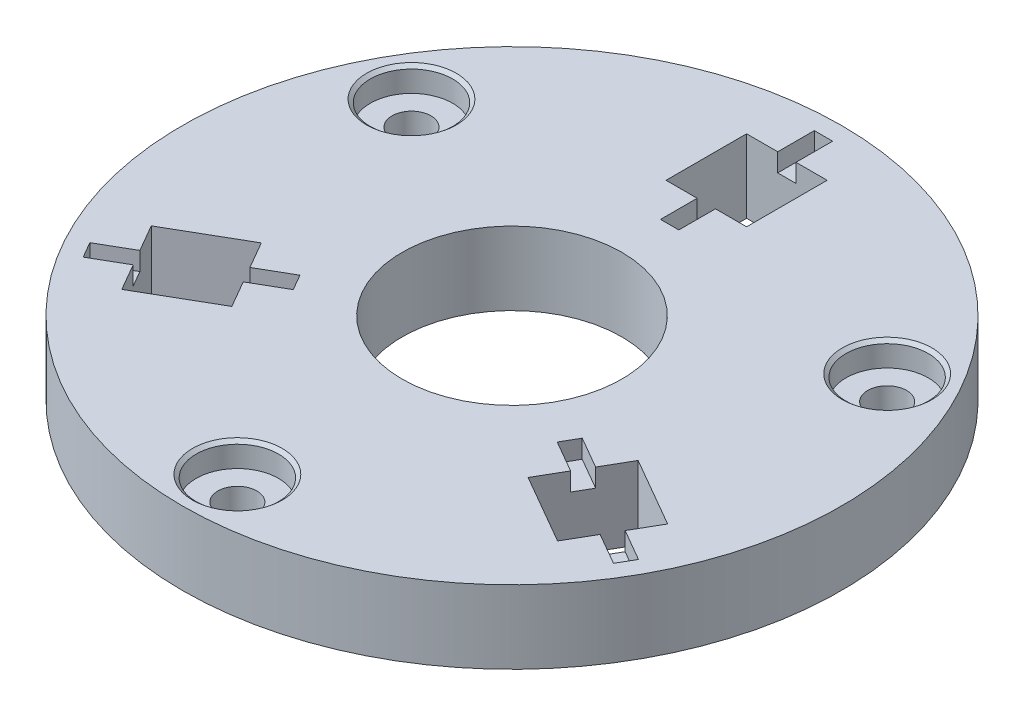
SolidWorks part; units mm, degrees
ref_plane "Front Plane" through (0, 0, 0) normal (0, 0, 1) x (1, 0, 0)
ref_plane "Top Plane" through (0, 0, 0) normal (0, 1, 0) x (1, 0, 0)
ref_plane "Right Plane" through (0, 0, 0) normal (1, 0, 0) x (0, 0, -1)
sketch "Sketch1" plane through (0, 0, 0) normal (0, 1, 0) x (1, 0, 0)
  circle A0 centre (0, 0) radius 57.15
  dimension "D1" = 114.3
extrude "Boss-Extrude1" add sketch "Sketch1" along normal blind 12.7
sketch "Sketch2" plane through (0, 12.7, 0) normal (0, 1, 0) x (1, 0, 0)
  circle A0 centre (0, 0) radius 19.05
  dimension "D1" = 38.1
extrude "Cut-Extrude1" cut sketch "Sketch2" against normal blind 76.2
hole_wizard "CBORE for 1/4 Binding Head Machine Screw1" positions "3DSketch1" profile "Sketch4" counterbore size "1/4" standard "ANSI Inch" end condition through all
sketch3d "3DSketch1"
  line L0 (-41.2445, 12.7, -23.8125) -> (41.2445, 12.7, -23.8125) construction
  line L2 (-41.2445, 12.7, -23.8125) -> (0, 12.7, 47.625) construction
  line L4 (0, 12.7, 47.625) -> (41.2445, 12.7, -23.8125) construction
  circle A2 centre (0, 12.7, 0) radius 47.625 construction
  point P0 (-41.2445, 12.7, -23.8125)
  point P4 (41.2445, 12.7, -23.8125)
  point P8 (0, 12.7, 47.625)
  point P33 (0, 60.325, 0)
  dimension "D1" = 95.25
sketch "Sketch4" plane through (-41.2445, 12.7, -23.8125) normal (1, 0, 0) x (0, 0, 1)
  line L0 (0, 0) -> (0, 12.7)
  line L1 (0, 12.7) -> (3.3782, 12.7)
  line L3 (3.3782, 12.7) -> (3.3782, 4.191)
  line L4 (7.1437, 4.191) -> (3.3782, 4.191)
  line L5 (7.1437, 4.191) -> (7.1437, 0.5328)
  line L6 (7.1437, 0.5328) -> (7.7788, 0)
  line L7 (7.7788, 0) -> (0, 0)
  line L8 (-7.1437, 0.5328) -> (-7.7788, 0) construction
  line L11 (0, -6.35) -> (0, 107.95) construction
  dimension "Thru Hole Dia." = 6.7564
  dimension "Thru Hole Depth" = 12.7
  dimension "C'Bore Dia." = 14.2875
  dimension "C'Bore Depth" = 4.191
  dimension "Near C'Sink Dia." = 15.5575
  dimension "Near C'Sink Angle" = 100
sketch "Sketch5" plane through (0, 12.7, 0) normal (0, 1, 0) x (1, 0, 0)
  line L0 (-44.7713, -17.7831) -> (-32.6729, -10.7981)
  line L5 (32.6729, -10.7981) -> (44.7713, -17.7831)
  line L6 (32.6729, -10.7981) -> (25.6879, -22.8965)
  line L7 (25.6879, -22.8965) -> (37.7863, -29.8815)
  line L8 (44.7713, -17.7831) -> (37.7863, -29.8815)
  line L13 (-6.985, 47.6647) -> (6.985, 47.6647)
  line L14 (-6.985, 47.6647) -> (-6.985, 33.6947)
  line L15 (-6.985, 33.6947) -> (6.985, 33.6947)
  line L16 (6.985, 47.6647) -> (6.985, 33.6947)
  line L17 (-32.6729, -10.7981) -> (-25.6879, -22.8965)
  line L18 (-25.6879, -22.8965) -> (-37.7863, -29.8815)
  line L19 (-37.7863, -29.8815) -> (-44.7713, -17.7831)
  line L20 (44.7713, -17.7831) -> (32.6729, -10.7981)
  line L22 (6.985, 42.2672) -> (6.985, 39.0922)
  line L26 (-6.985, 42.2672) -> (-6.985, 39.0922)
  line L29 (44.7713, -17.7831) -> (37.7863, -29.8815)
  line L30 (37.7863, -29.8815) -> (25.6879, -22.8965)
  line L31 (32.6729, -10.7981) -> (25.6879, -22.8965)
  line L32 (40.0969, -15.0844) -> (37.3473, -13.4969)
  line L36 (33.1119, -27.1828) -> (30.3623, -25.5953)
  line L40 (-37.7863, -29.8815) -> (-25.6879, -22.8965)
  line L41 (-37.7863, -29.8815) -> (-44.7713, -17.7831)
  line L42 (-44.7713, -17.7831) -> (-32.6729, -10.7981)
  line L43 (-25.6879, -22.8965) -> (-32.6729, -10.7981)
  line L44 (-33.1119, -27.1828) -> (-30.3623, -25.5953)
  line L48 (-40.0969, -15.0844) -> (-37.3473, -13.4969)
  circle A0 centre (0, 0) radius 41.275 construction
  point P2 (-38.7221, -14.2906)
  point P15 (6.985, 40.6797)
  point P16 (0, 47.6647)
  point P18 (-31.7371, -26.389)
  point P23 (38.7221, -14.2906)
  point P24 (31.7371, -26.389)
  point P57 (0, 0)
  dimension "D2" = 82.55
  dimension "D1" = 120
  dimension "D3" = 120
  dimension "D4" = 13.97
extrude "Cut-Extrude2" cut sketch "Sketch5" against normal blind 12.7 contours L16 L13 L14 L15 | L19 L18 L40 L17 L0 L42 | L8 L5 L20 L6 L7 L30 | L22
sketch "Sketch7" plane through (0, 12.7, 0) normal (0, 1, 0) x (1, 0, 0)
  line L0 (-6.985, 47.6647) -> (6.985, 47.6647) construction
  line L1 (-1.5875, 47.6647) -> (1.5875, 47.6647)
  line L2 (-1.5875, 47.6647) -> (-1.5875, 54.0147)
  line L3 (-1.5875, 54.0147) -> (1.5875, 54.0147)
  line L4 (1.5875, 47.6647) -> (1.5875, 54.0147)
  line L5 (-6.985, 33.6947) -> (6.985, 33.6947) construction
  line L6 (-1.5875, 33.6947) -> (1.5875, 33.6947)
  line L7 (-1.5875, 33.6947) -> (-1.5875, 27.3447)
  line L8 (-1.5875, 27.3447) -> (1.5875, 27.3447)
  line L9 (1.5875, 33.6947) -> (1.5875, 27.3447)
  line L10 (42.0726, -22.4575) -> (47.5718, -25.6325)
  line L11 (42.0726, -22.4575) -> (40.4851, -25.2071)
  line L12 (40.4851, -25.2071) -> (45.9843, -28.3821)
  line L13 (47.5718, -25.6325) -> (45.9843, -28.3821)
  line L14 (29.9742, -15.4725) -> (24.4749, -12.2975)
  line L15 (29.9742, -15.4725) -> (28.3867, -18.2221)
  line L16 (28.3867, -18.2221) -> (22.8874, -15.0471)
  line L17 (24.4749, -12.2975) -> (22.8874, -15.0471)
  line L18 (-40.4851, -25.2071) -> (-45.9843, -28.3821)
  line L19 (-40.4851, -25.2071) -> (-42.0726, -22.4575)
  line L20 (-42.0726, -22.4575) -> (-47.5718, -25.6325)
  line L21 (-45.9843, -28.3821) -> (-47.5718, -25.6325)
  line L22 (-28.3867, -18.2221) -> (-22.8874, -15.0471)
  line L23 (-28.3867, -18.2221) -> (-29.9742, -15.4725)
  line L24 (-29.9742, -15.4725) -> (-24.4749, -12.2975)
  line L25 (-22.8874, -15.0471) -> (-24.4749, -12.2975)
  point P12 (0, 47.6647)
  point P13 (0, 54.0147)
  point P33 (0, 0)
  dimension "D1" = 3.175
  dimension "D2" = 6.35
  dimension "D3" = 3
extrude "Cut-Extrude4" cut sketch "Sketch7" against normal blind 3.175
